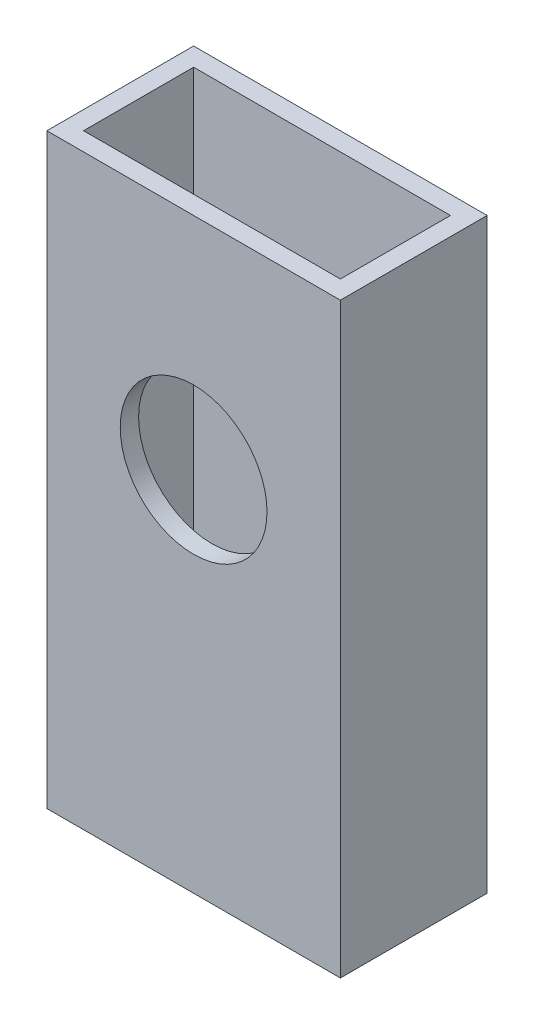
SolidWorks part; units mm, degrees
ref_plane "Front Plane" through (0, 0, 0) normal (0, 0, 1) x (1, 0, 0)
ref_plane "Top Plane" through (0, 0, 0) normal (0, 1, 0) x (1, 0, 0)
ref_plane "Right Plane" through (0, 0, 0) normal (1, 0, 0) x (0, 0, -1)
sketch "Sketch1" plane through (0, 0, 0) normal (0, 0, 1) x (1, 0, 0)
  line L1 (0, 0) -> (50.8, 0)
  line L2 (0, 0) -> (0, 101.6)
  line L3 (0, 101.6) -> (50.8, 101.6)
  line L4 (50.8, 0) -> (50.8, 101.6)
  dimension "D1" = 50.8
  dimension "D2" = 101.6
extrude "Boss-Extrude1" add sketch "Sketch1" along normal blind 25.4
sketch "Sketch2" plane through (0, 0, 0) normal (0, -1, 0) x (1, 0, 0)
  line L0 (0, 25.4) -> (50.8, 25.4) construction
  line L1 (3.175, 22.225) -> (47.625, 22.225)
  line L2 (3.175, 22.225) -> (3.175, 3.175)
  line L3 (3.175, 3.175) -> (47.625, 3.175)
  line L4 (47.625, 22.225) -> (47.625, 3.175)
  line L5 (50.8, 25.4) -> (50.8, 0) construction
  line L6 (0, 0) -> (50.8, 0) construction
  line L7 (0, 25.4) -> (0, 0) construction
  dimension "D1" = 3.175
  dimension "D2" = 3.175
  dimension "D3" = 3.175
  dimension "D4" = 3.175
extrude "Cut-Extrude1" cut sketch "Sketch2" against normal through all
sketch "Sketch3" plane through (0, 0, 25.4) normal (0, 0, 1) x (1, 0, 0)
  line L0 (50.8, 101.6) -> (0, 101.6) construction
  circle A0 centre (25.4, 63.5) radius 12.7
  dimension "D1" = 25.4
  dimension "D2" = 38.1
extrude "Cut-Extrude2" cut sketch "Sketch3" against normal blind 6.35 contours A0
